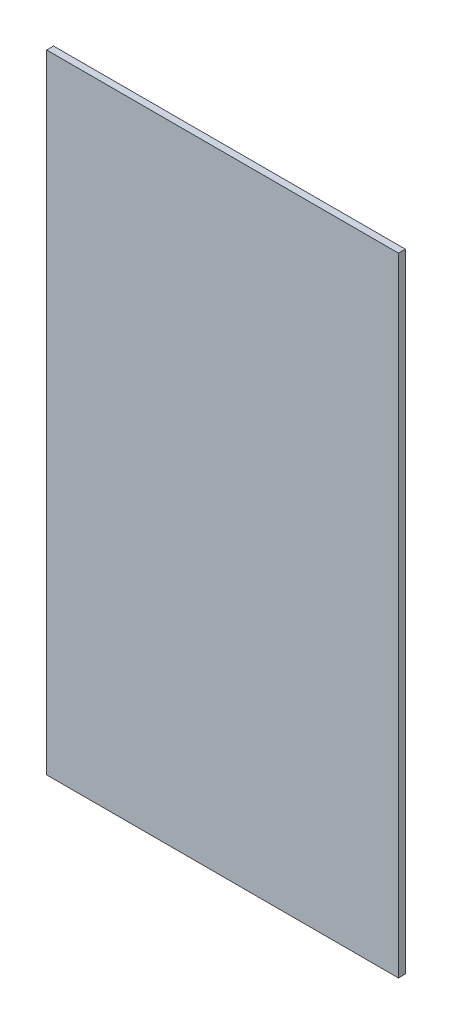
SolidWorks part; units mm, degrees
ref_plane "Front Plane" through (0, 0, 0) normal (0, 0, 1) x (1, 0, 0)
ref_plane "Top Plane" through (0, 0, 0) normal (0, 1, 0) x (1, 0, 0)
ref_plane "Right Plane" through (0, 0, 0) normal (1, 0, 0) x (0, 0, -1)
sketch "Sketch1" plane through (0, 0, 0) normal (0, 0, 1) x (1, 0, 0)
  line L18 (22.5, 22.5) -> (277.5, 22.5)
  line L19 (277.5, 22.5) -> (277.5, 477.5)
  line L20 (22.5, 477.5) -> (22.5, 22.5)
  line L21 (277.5, 477.5) -> (22.5, 477.5)
  line L22 (22.5, 22.5) -> (277.5, 22.5)
  line L23 (277.5, 22.5) -> (277.5, 477.5)
  line L24 (22.5, 477.5) -> (22.5, 22.5)
  line L25 (277.5, 477.5) -> (22.5, 477.5)
  dimension "D1" = 2.5
extrude "Boss-Extrude1" add sketch "Sketch1" against normal blind 5
